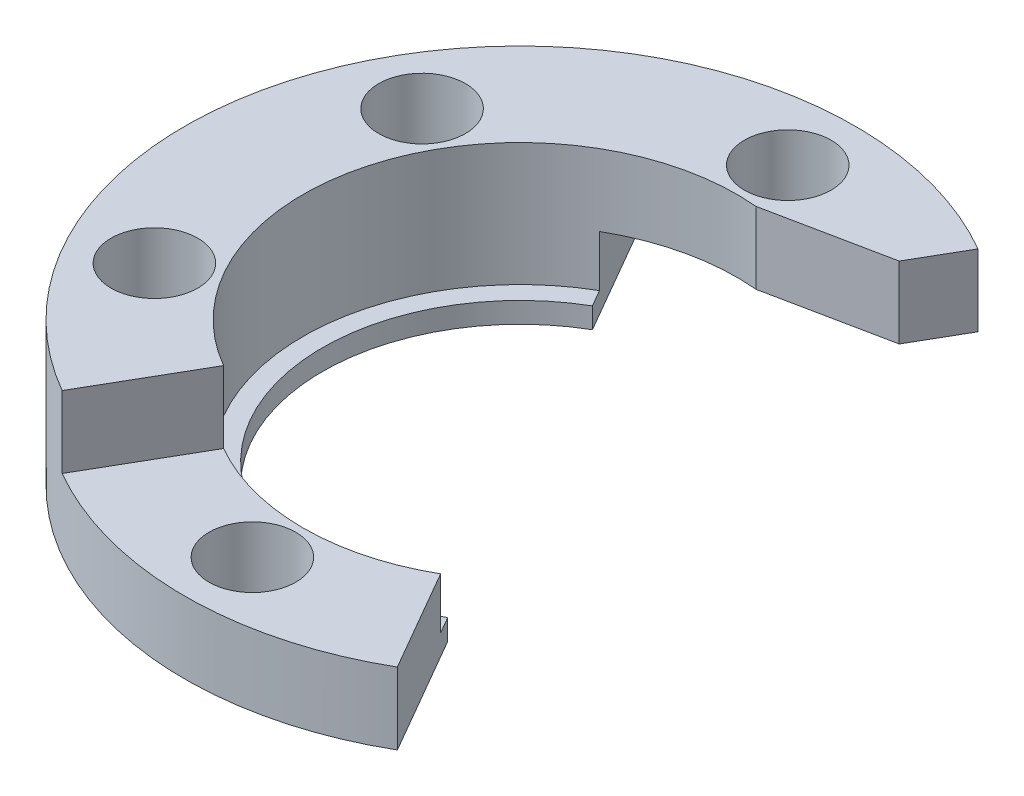
SolidWorks part; units mm, degrees
ref_plane "Front Plane" through (0, 0, 0) normal (0, 0, 1) x (1, 0, 0)
ref_plane "Top Plane" through (0, 0, 0) normal (0, 1, 0) x (1, 0, 0)
ref_plane "Right Plane" through (0, 0, 0) normal (1, 0, 0) x (0, 0, -1)
sketch "Sketch1" plane through (0, 0, 0) normal (0, 1, 0) x (1, 0, 0)
  circle A0 centre (0, 0) radius 16.891
  dimension "D1" = 33.782
extrude "Extrude1" add sketch "Sketch1" along normal blind 7.239
sketch "Sketch2" plane through (0, 0, 0) normal (0, -1, 0) x (1, 0, 0)
  circle A0 centre (0, 0) radius 10.9347
  circle A1 centre (0, 0) radius 16.891 construction
  dimension "D1" = 5.9563
extrude "Extrude2" cut sketch "Sketch2" against normal through all
sketch "Sketch3" plane through (0, 0, 0) normal (0, -1, 0) x (1, 0, 0)
  circle A0 centre (0, 0) radius 9.9568
  circle A1 centre (0, 0) radius 10.9347
  circle A2 centre (0, 0) radius 16.891 construction
  circle A3 centre (0, 0) radius 10.9347 construction
  dimension "D1" = 6.9342
extrude "Extrude3" add sketch "Sketch3" against normal blind 1.0414
sketch "Sketch4" plane through (0, 7.239, 0) normal (0, 1, 0) x (1, 0, 0)
  circle A0 centre (0, 13.4874) radius 2.1844
  dimension "D1" = 4.3688
  dimension "D2" = 13.4874
extrude "Extrude4" cut sketch "Sketch4" against normal through all
pattern_circular "CirPattern1" count 6 over 360 about axis through (0, 0, 0) along (0, 1, 0) of "Extrude4"
sketch "Sketch7" plane through (0, 7.239, 0) normal (0, 1, 0) x (1, 0, 0)
  line L0 (0, 0) -> (16.891, 29.2561)
  line L1 (16.891, 29.2561) -> (16.891, -29.2561)
  line L2 (16.891, 0) -> (0, 0) construction
  line L3 (0, 0) -> (16.891, -29.2561)
  circle A0 centre (0, 0) radius 16.891 construction
  dimension "D1" = 120
extrude "Extrude6" cut sketch "Sketch7" against normal through all
sketch "Sketch8" plane through (0, 7.239, 0) normal (0, 1, 0) x (1, 0, 0)
  line L0 (0, 0) -> (9.752, -16.891)
  line L1 (-9.752, -16.891) -> (9.752, -16.891)
  line L2 (-9.752, -16.891) -> (0, 0)
  line L4 (5.4673, -9.4697) -> (8.4455, -14.628) construction
  arc A0 (8.4455, 14.628) -> (8.4455, -14.628) centre (0, 0) ccw construction
  dimension "D1" = 60
extrude "Extrude7" cut sketch "Sketch8" against normal blind 3.6195
sketch "Sketch9" plane through (0, 0, 0) normal (0, -1, 0) x (1, 0, 0)
  line L0 (0, 0) -> (9.752, -16.891)
  line L1 (9.752, -16.891) -> (-9.752, -16.891)
  line L2 (-9.752, -16.891) -> (0, 0)
  line L4 (8.4455, -14.628) -> (5.4673, -9.4697) construction
  arc A0 (8.4455, 14.628) -> (8.4455, -14.628) centre (0, 0) ccw construction
  dimension "D1" = 60
extrude "Extrude8" cut sketch "Sketch9" against normal blind 3.6195
sketch "Sketch13" plane through (0, 3.6195, 0) normal (0, 1, 0) x (1, 0, 0)
  line L0 (0.9986, 10.889) -> (6.9927, 12.1116)
  line L1 (-4.9784, 8.6228) -> (4.9784, -8.6228) construction
  line L2 (4.9784, -8.6228) -> (0.9986, 10.889) construction
  line L3 (8.4455, 14.628) -> (5.4673, 9.4697) construction
  line L4 (0.9986, 10.889) -> (4.9784, -8.6228)
  line L5 (6.9927, 12.1116) -> (4.9784, -8.6228)
  arc A0 (5.4673, 9.4697) -> (-5.4673, -9.4697) centre (0, 0) ccw construction
  point P6 (0, 13.4874)
  dimension "D1" = 19.9136
extrude "Extrude12" cut sketch "Sketch13" along normal through all
fillet "Fillet4" [suppressed] radius 0.254
